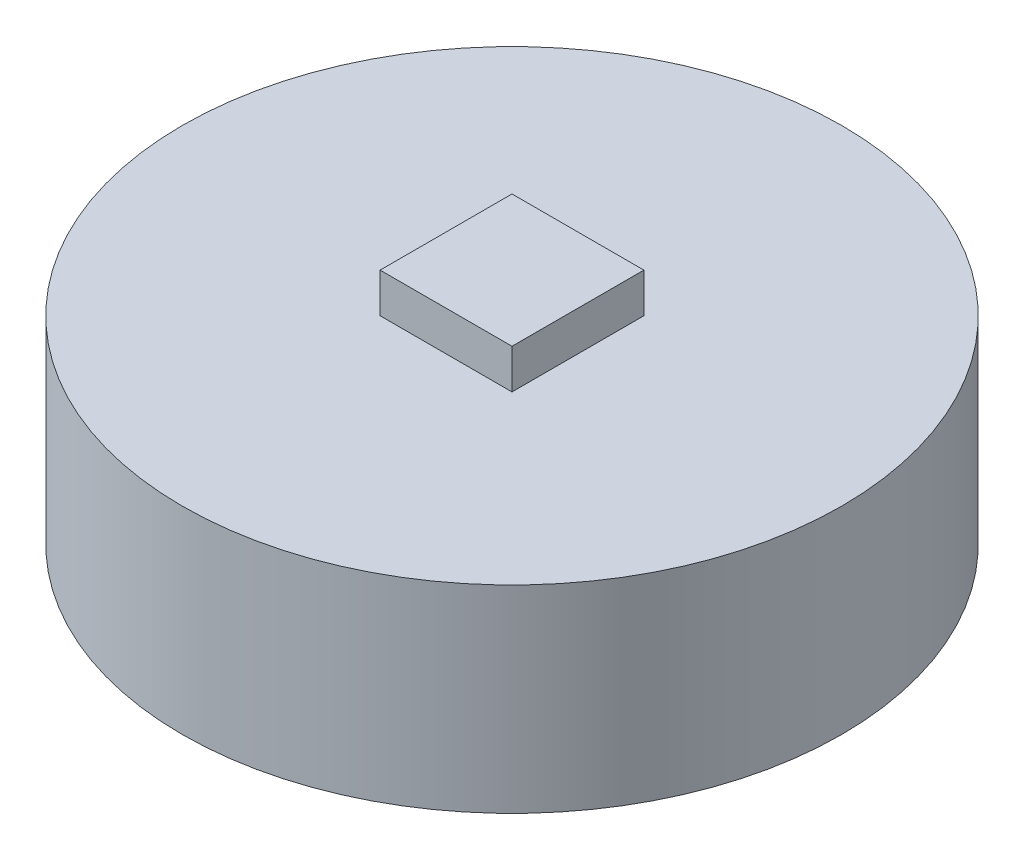
SolidWorks part; units mm, degrees
ref_plane "Front Plane" through (0, 0, 0) normal (0, 0, 1) x (1, 0, 0)
ref_plane "Top Plane" through (0, 0, 0) normal (0, 1, 0) x (1, 0, 0)
ref_plane "Right Plane" through (0, 0, 0) normal (1, 0, 0) x (0, 0, -1)
sketch "Sketch1" plane through (0, 0, 0) normal (0, 1, 0) x (1, 0, 0)
  circle A0 centre (0, 0) radius 25
  dimension "D1" = 50
extrude "Boss-Extrude1" add sketch "Sketch1" along normal blind 15
sketch "Sketch2" plane through (0, 15, 0) normal (0, 1, 0) x (1, 0, 0)
  line L1 (-5, -5) -> (5, -5)
  line L2 (-5, -5) -> (-5, 5)
  line L3 (-5, 5) -> (5, 5)
  line L4 (5, -5) -> (5, 5)
  line L5 (-5, -5) -> (5, 5) construction
  line L6 (-5, 5) -> (5, -5) construction
  point P0 (0, 0)
  dimension "D1" = 10
  dimension "D2" = 10
extrude "Boss-Extrude2" add sketch "Sketch2" along normal blind 3
sketch "Sketch3" plane through (0, 0, 0) normal (0, -1, 0) x (1, 0, 0)
  line L1 (5, 5) -> (-5, 5)
  line L2 (5, 5) -> (5, -5)
  line L3 (5, -5) -> (-5, -5)
  line L4 (-5, 5) -> (-5, -5)
  line L5 (5, 5) -> (-5, -5) construction
  line L6 (5, -5) -> (-5, 5) construction
  point P0 (0, 0)
  dimension "D1" = 10
  dimension "D2" = 10
extrude "Cut-Extrude1" cut sketch "Sketch3" against normal blind 3
